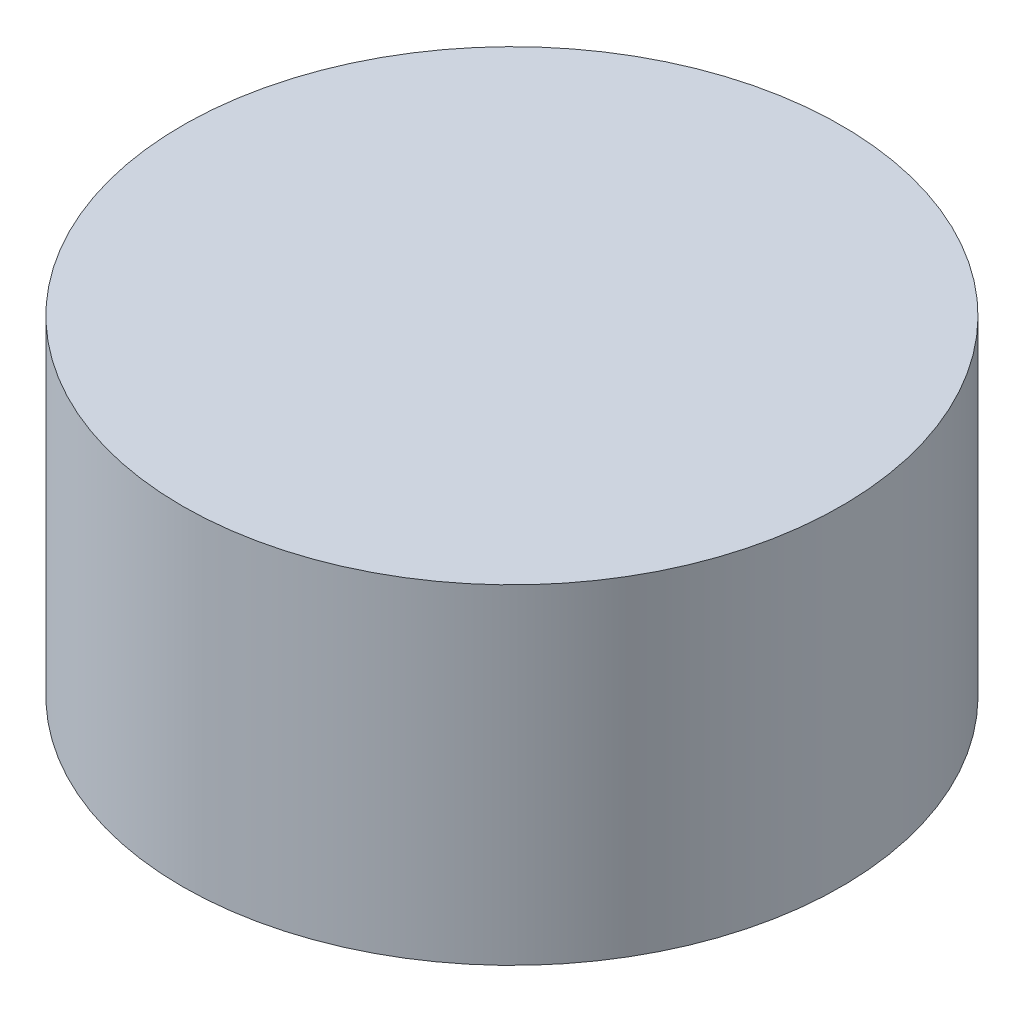
SolidWorks part; units mm, degrees
ref_plane "Front Plane" through (0, 0, 0) normal (0, 0, 1) x (1, 0, 0)
ref_plane "Top Plane" through (0, 0, 0) normal (0, 1, 0) x (1, 0, 0)
ref_plane "Right Plane" through (0, 0, 0) normal (1, 0, 0) x (0, 0, -1)
sketch "Sketch1" plane through (0, 0, 0) normal (0, 1, 0) x (1, 0, 0)
  circle A0 centre (0, 0) radius 63.5
extrude "Boss-Extrude1" add sketch "Sketch1" along normal blind 63.5
